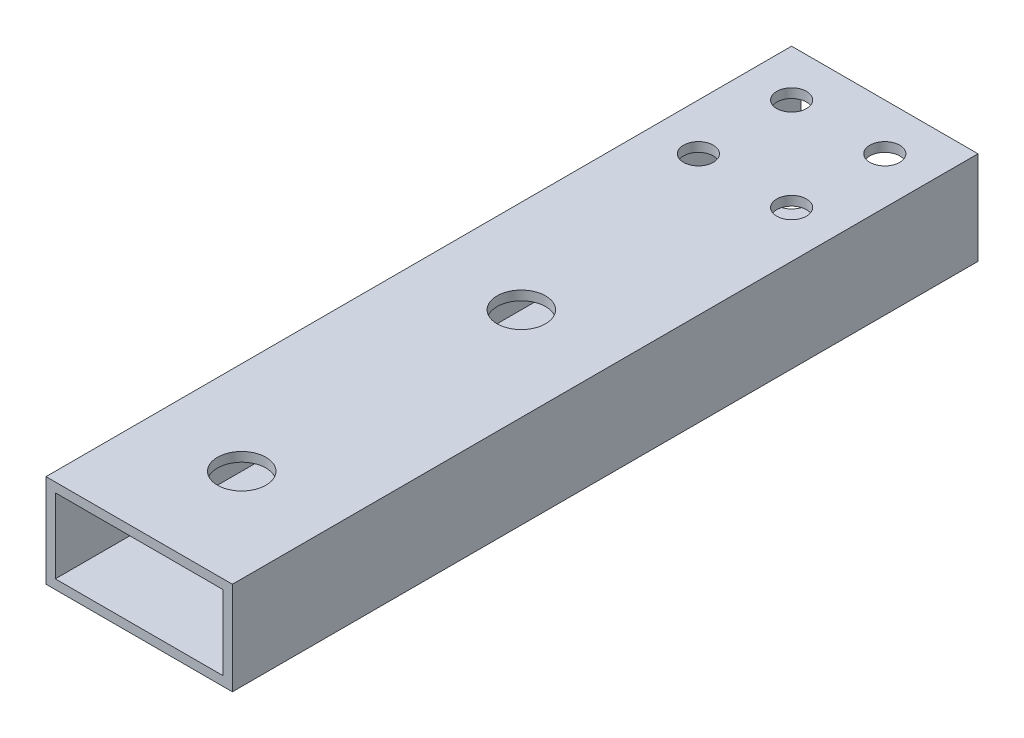
SolidWorks part; units mm, degrees
ref_plane "前视基准面" through (0, 0, 0) normal (0, 0, 1) x (1, 0, 0)
ref_plane "上视基准面" through (0, 0, 0) normal (0, 1, 0) x (1, 0, 0)
ref_plane "右视基准面" through (0, 0, 0) normal (1, 0, 0) x (0, 0, -1)
other "Configuration Table"
sketch "草图1" plane through (0, 0, 0) normal (0, 0, 1) x (1, 0, 0)
  line L1 (0, 0) -> (20, 0)
  line L2 (0, 0) -> (0, -10)
  line L3 (0, -10) -> (20, -10)
  line L4 (20, 0) -> (20, -10)
  dimension "D1" = 10
  dimension "D2" = 20
extrude "拉伸-薄壁1" add sketch "草图1" along normal blind 80 thin
sketch "草图3" plane through (0, 0, 0) normal (0, 1, 0) x (1, 0, 0)
  line L0 (0, -10) -> (20, -10) construction
  line L1 (0, -80) -> (0, 0) construction
  line L2 (20, -80) -> (20, 0) construction
  line L3 (10, 0) -> (10, -10) construction
  line L4 (20, 0) -> (0, 0) construction
  line L5 (10, -80) -> (10, -69) construction
  line L6 (20, -80) -> (0, -80) construction
  circle A0 centre (5, -5) radius 1.6
  circle A1 centre (15, -5) radius 1.6
  circle A2 centre (15, -15) radius 1.6
  circle A3 centre (5, -15) radius 1.6
  circle A4 centre (10, -69) radius 2.6
  circle A5 centre (10, -39) radius 2.6
  dimension "D1" = 3.2
  dimension "D5" = 5.2
  dimension "D7" = 5.2
  dimension "D2" = 5
  dimension "D3" = 5
  dimension "D4" = 10
  dimension "D6" = 11
  dimension "D8" = 30
  dimension "D9" = 10
extrude "切除-拉伸1" cut sketch "草图3" against normal through all
